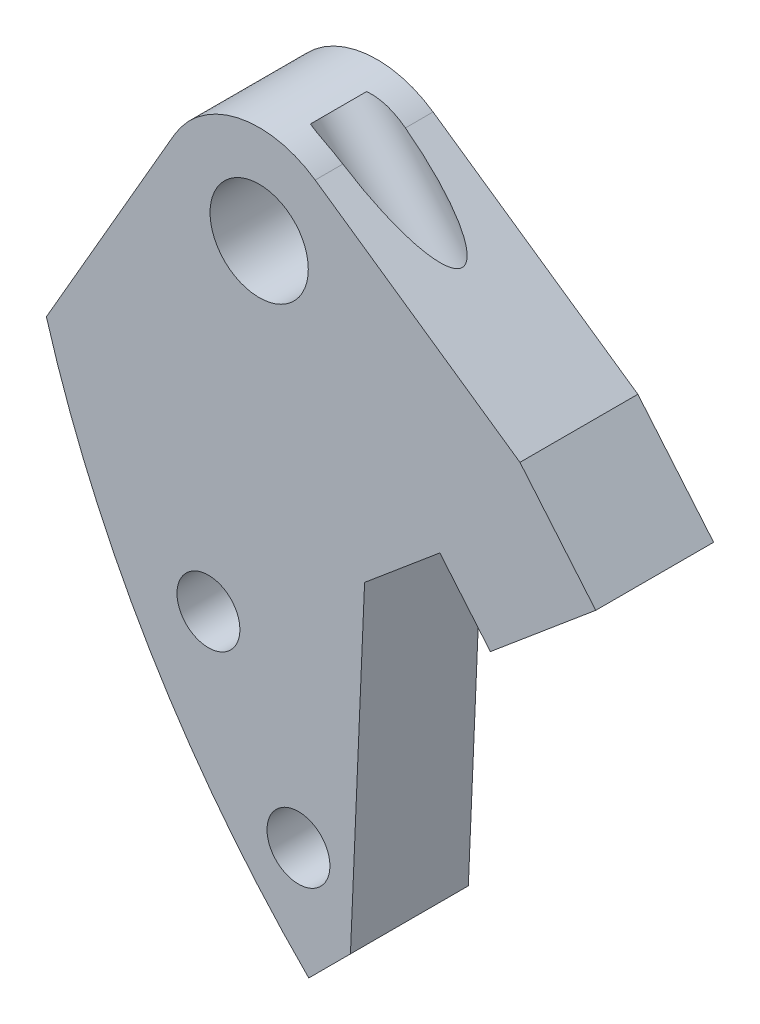
SolidWorks part; units mm, degrees
ref_plane "前视基准面" through (0, 0, 0) normal (0, 0, 1) x (1, 0, 0)
ref_plane "上视基准面" through (0, 0, 0) normal (0, 1, 0) x (1, 0, 0)
ref_plane "右视基准面" through (0, 0, 0) normal (1, 0, 0) x (0, 0, -1)
sketch "草图2" plane through (0, 0, 0) normal (0, 0, 1) x (1, 0, 0)
  line L0 (-35.3553, -35.3553) -> (0, 0) construction
  line L1 (0, 0) -> (-50, 0) construction
  line L2 (-50, 0) -> (-53, 0) construction
  line L3 (-37.4767, -37.4767) -> (-35.3553, -35.3553)
  line L4 (-35.3553, -35.3553) -> (-34.635, -18.619)
  line L5 (0, 0) -> (-23.9134, -20.0657) construction
  line L6 (-25.5525, -16.2195) -> (-28.1236, -13.1553) construction
  line L8 (-25.4425, -10.9055) -> (-22.8713, -13.9697)
  line L9 (-22.8713, -13.9697) -> (-28.2336, -18.4692)
  line L10 (-28.2336, -18.4692) -> (-30.8048, -15.405)
  line L11 (-44.3301, -3.75) -> (-50.8304, -15.0089)
  line L13 (-25.4425, -10.9055) -> (-26.7281, -9.3734)
  line L14 (-26.7281, -9.3734) -> (-37.1496, -2.1421)
  line L16 (-30.8048, -15.405) -> (-34.635, -18.619)
  arc A0 (-50, 0) -> (-35.3553, -35.3553) centre (0, 0) ccw construction
  arc A2 (-37.1496, -2.1421) -> (-44.3301, -3.75) centre (-40, -6.25) ccw
  circle A3 centre (-40, -6.25) radius 2.5
  arc A4 (-37.4767, -37.4767) -> (-50.8304, -15.0089) centre (0, 0) cw
  dimension "D1" = 50
  dimension "D4" = 10
  dimension "D6" = 6.25
  dimension "D7" = 40
  dimension "D8" = 5
  dimension "D13" = 53
  dimension "D15" = 60
  dimension "D16" = 4
  dimension "D2" = 3
  dimension "D3" = 45
  dimension "D5" = 40
  dimension "D9" = 7
  dimension "D10" = 2
  dimension "D11" = 30
  dimension "D12" = 4
  dimension "D14" = 5
extrude "凸台-拉伸1" add sketch "草图2" along normal blind 6
sketch "草图3" plane through (0, 0, 0) normal (0, 0, -1) x (-1, 0, 0)
  circle A0 centre (42.5828, -23.8737) radius 1.6
  circle A1 centre (38, -32) radius 1.6
  dimension "D1" = 3.2
  dimension "D4" = 32
  dimension "D5" = 38
extrude "切除-拉伸1" cut sketch "草图3" against normal blind 10
sketch "草图4" plane through (-2.5712, 3.0642, 0) normal (0.6428, -0.766, 0) x (0.766, 0.6428, 0)
  line L0 (-26.5, 3) -> (-33.5, 3) construction
  line L1 (-26.5, 6) -> (-26.5, 0) construction
  line L2 (-33.5, 6) -> (-33.5, 0) construction
  circle A0 centre (-30, 3) radius 1.6
  dimension "D1" = 3.2
extrude "切除-拉伸2" cut sketch "草图4" against normal blind 20
